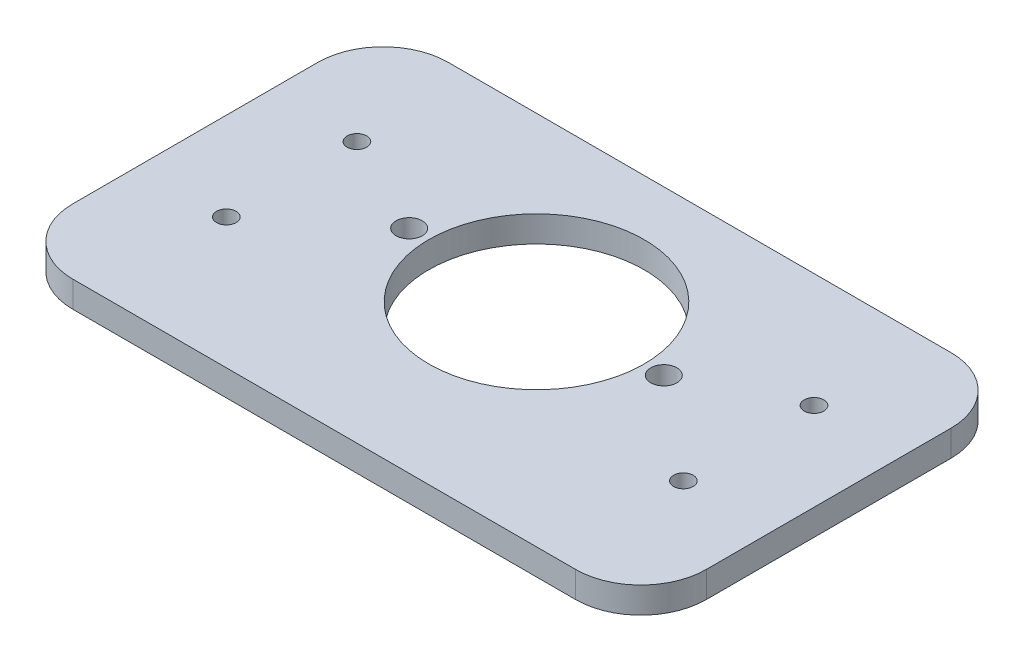
SolidWorks part; units mm, degrees
ref_plane "Спереди" through (0, 0, 0) normal (0, 0, 1) x (1, 0, 0)
ref_plane "Сверху" through (0, 0, 0) normal (0, 1, 0) x (1, 0, 0)
ref_plane "Справа" through (0, 0, 0) normal (1, 0, 0) x (0, 0, -1)
other "Configuration Table"
sketch "Эскиз1" plane through (0, 0, 0) normal (0, 1, 0) x (1, 0, 0)
  line L0 (48.5, 0) -> (48.5, 57.5) construction
  line L1 (0, 0) -> (97, 0)
  line L2 (0, 0) -> (0, 57.5)
  line L3 (0, 57.5) -> (97, 57.5)
  line L4 (97, 0) -> (97, 57.5)
  circle A0 centre (48.5, 32.5) radius 16.5
  circle A1 centre (29, 32.5) radius 2
  circle A2 centre (68, 32.5) radius 2
  dimension "D2" = 33
  dimension "D6" = 4
  dimension "D1" = 39
  dimension "D3" = 57.5
  dimension "D4" = 97
  dimension "D5" = 32.5
extrude "Бобышка-Вытянуть1" add sketch "Эскиз1" along normal blind 4
fillet "Скругление1" radius 10 4 edges at (0, 2, 0) (97, 2, 0) (97, 2, -57.5) (0, 2, -57.5)
sketch "Эскиз2" plane through (0, 4, 0) normal (0, 1, 0) x (1, 0, 0)
  line L0 (48.5, 57.5) -> (48.5, 0) construction
  circle A0 centre (13.5, 20) radius 1.5
  circle A1 centre (13.5, 40) radius 1.5
  circle A2 centre (83.5, 40) radius 1.5
  circle A3 centre (83.5, 20) radius 1.5
  dimension "D2" = 70
  dimension "D3" = 20
extrude "Вырез-Вытянуть1" cut sketch "Эскиз2" against normal blind 10
